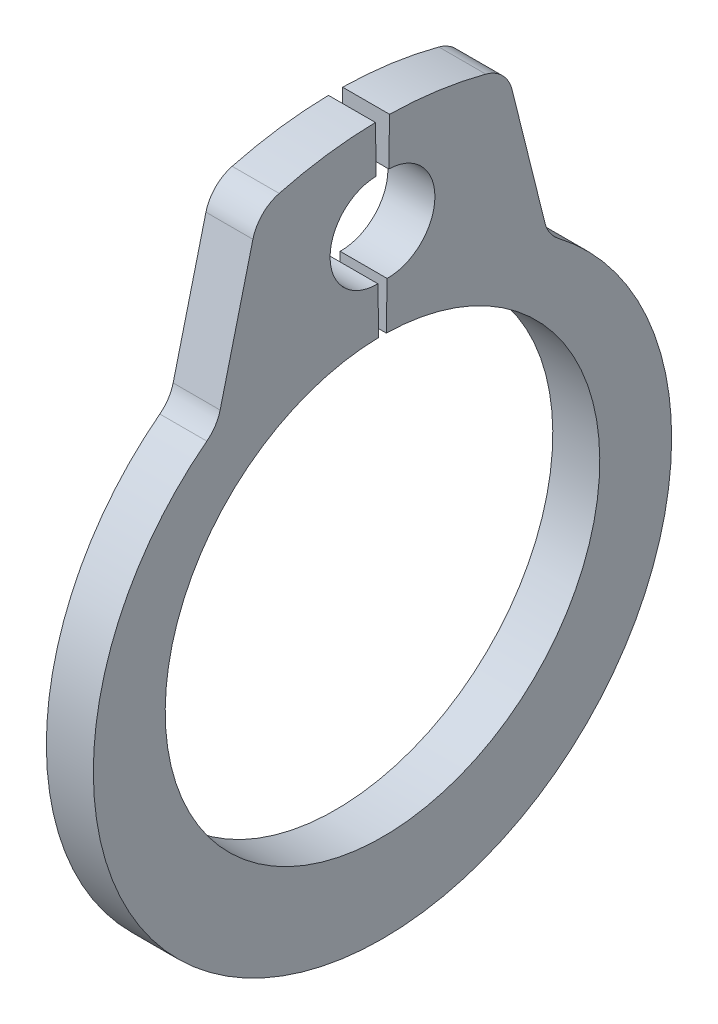
SolidWorks part; units mm, degrees
material "Cast Carbon Steel"
ref_plane "Front" through (0, 0, 0) normal (0, 0, 1) x (1, 0, 0)
ref_plane "Top" through (0, 0, 0) normal (0, 1, 0) x (1, 0, 0)
ref_plane "Right" through (0, 0, 0) normal (1, 0, 0) x (0, 0, -1)
sketch "Sketch1" plane through (0, 0, 0) normal (1, 0, 0) x (0, 0, -1)
  line L0 (0, 0) -> (0, 3.7) construction
  line L1 (-0.0646, 3.6994) -> (-0.1204, 6.8989) construction
  line L2 (-0.1204, 6.8989) -> (-2.0453, 6.8654) construction
  line L3 (-2.0453, 6.8654) -> (-2.8195, 3.7604) construction
  line L4 (0.1204, 6.8989) -> (0.0646, 3.6994) construction
  line L5 (0.1204, 6.8989) -> (2.0453, 6.8654) construction
  line L6 (2.0453, 6.8654) -> (2.8195, 3.7604) construction
  line L7 (-2.8195, 3.7604) -> (-2.2196, 2.9603) construction
  line L8 (2.8195, 3.7604) -> (2.2196, 2.9603) construction
  line L9 (0, -3.7) -> (0, -5.2) construction
  line L10 (-2.0453, 6.8654) -> (-0.0646, 3.6994) construction
  line L11 (0.0646, 3.6994) -> (0.0785, 4.4993)
  line L12 (0, 3.7) -> (0, 6.9) construction
  line L13 (2.1199, 6.5663) -> (2.8195, 3.7604)
  line L14 (-2.1199, 6.5663) -> (-2.8195, 3.7604)
  line L16 (0.1065, 6.0991) -> (0.1204, 6.8989)
  line L17 (-0.1065, 6.0991) -> (-0.1204, 6.8989)
  line L18 (-0.0785, 4.4993) -> (-0.0646, 3.6994)
  circle A0 centre (0, 0) radius 3.7 construction
  arc A1 (-0.0646, 3.6994) -> (0.0646, 3.6994) centre (0, 0) ccw
  circle A2 centre (0, -0.2762) radius 4.9238 construction
  arc A3 (0.1065, 6.0991) -> (0.0785, 4.4993) centre (0.0925, 5.2992) cw
  arc A4 (-0.0785, 4.4993) -> (-0.1065, 6.0991) centre (-0.0925, 5.2992) cw
  arc A6 (-2.8195, 3.7604) -> (2.8195, 3.7604) centre (0, -0.2762) ccw
  arc A7 (0.1204, 6.8989) -> (2.1199, 6.5663) centre (0, 0) cw
  arc A8 (-0.1204, 6.8989) -> (-2.1199, 6.5663) centre (0, 0) ccw
  dimension "A" = 7.4
  dimension "Smin" = 1
  dimension "D1" = 75
  dimension "Angle" = 1
  dimension "H" = 3.2
  dimension "D2" = 1.6
extrude "Extrude1" add sketch "Sketch1" along normal mid plane 0.8
fillet "Fillet1" radius 0.625 4 edges at (0, 3.7604, 2.8195) (0, 6.5663, 2.1199) (0, 6.5663, -2.1199) (0, 3.7604, -2.8195)
sketch "Sketch2" plane through (0, 0, 0) normal (0, 0, 1) x (1, 0, 0)
  line L0 (-2.25, 0) -> (6.75, 0)
  line L1 (6.75, 0) -> (6.75, -4)
  line L2 (-0.45, -4) -> (-2.05, -4)
  line L3 (6.75, -4) -> (0.45, -4)
  line L4 (0.45, -4) -> (0.45, -3.8)
  line L5 (0.45, -3.8) -> (-0.45, -3.8)
  line L6 (-0.45, -3.8) -> (-0.45, -4)
  line L7 (-0.45, -4) -> (-2.25, -4) construction
  line L8 (-2.25, -4) -> (-2.25, 0) construction
  line L9 (0, -3.8) -> (0, 0) construction
  line L10 (6.75, 0) -> (14.0551, 0) construction
  line L11 (-2.05, -4) -> (-2.25, -3.8)
  line L12 (-2.25, -3.8) -> (-2.25, 0)
  dimension "D2" = 9
  dimension "D3" = 2.25
  dimension "D1" = 45
revolve "Revolve1" [suppressed] add sketch "Sketch2" angle 360 about L10
equation "\"D2@Sketch2\" = \"W@Sketch2\"*10"
equation "\"D3@Sketch2\" = \"D2@Sketch2\"/4"
equation "\"Smin@Sketch1\" = \"Smax@Sketch1\"/1.5"
equation "\"D2@Sketch1\" = \"H@Sketch1\"/2"
